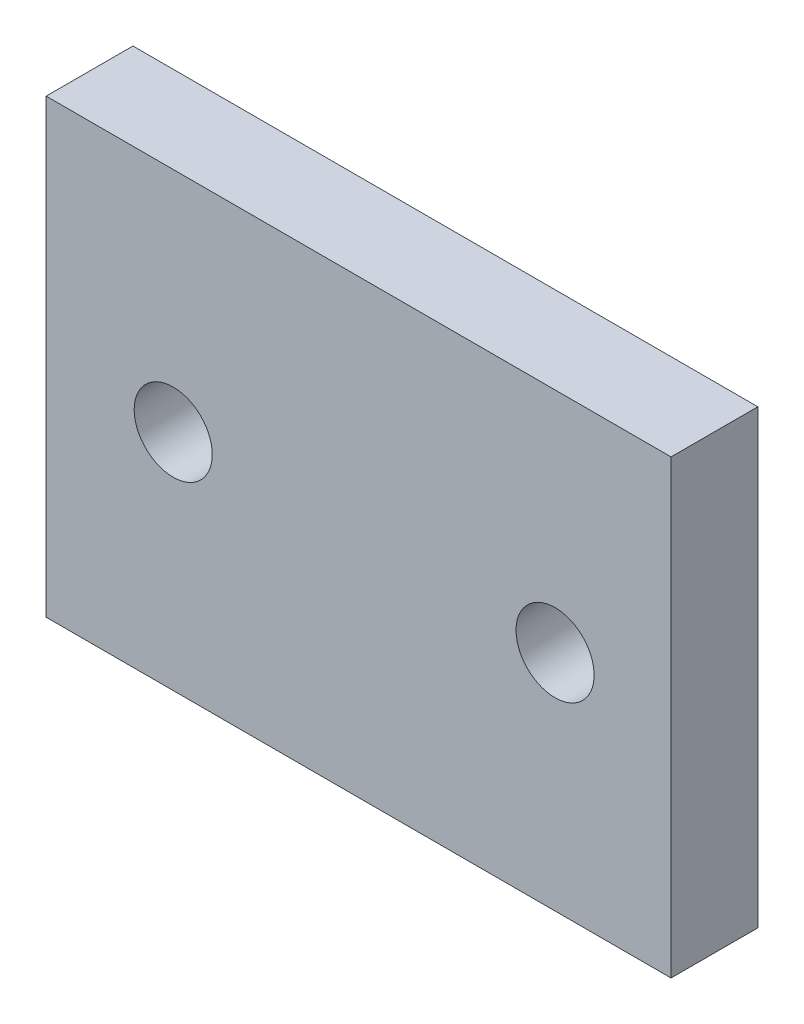
SolidWorks part; units mm, degrees
ref_plane "Plan de face" through (0, 0, 0) normal (0, 0, 1) x (1, 0, 0)
ref_plane "Plan de dessus" through (0, 0, 0) normal (0, 1, 0) x (1, 0, 0)
ref_plane "Plan de droite" through (0, 0, 0) normal (1, 0, 0) x (0, 0, -1)
sketch "Esquisse1" plane through (0, 0, 0) normal (0, 0, 1) x (1, 0, 0)
  line L1 (-18, -13) -> (18, -13)
  line L2 (-18, -13) -> (-18, 13)
  line L3 (-18, 13) -> (18, 13)
  line L4 (18, -13) -> (18, 13)
  line L5 (-18, -13) -> (18, 13) construction
  line L6 (-18, 13) -> (18, -13) construction
  point P0 (0, 0)
  dimension "D1" = 36
  dimension "D2" = 26
extrude "Boss.-Extru.1" add sketch "Esquisse1" along normal blind 5
hole_wizard "Dégagement M41" positions "Esquisse3" profile "Esquisse2" hole size "M4" standard "JIS" end condition through all
sketch "Esquisse3" plane through (0, 0, 0) normal (0, 0, -1) x (-1, 0, 0)
  point P0 (-11.3189, -0.1078)
  point P2 (10.6811, -0.105)
sketch "Esquisse2" plane through (11.3189, -0.1078, 0) normal (1, 0, 0) x (0, 1, 0)
  line L0 (0, 0) -> (0, 5)
  line L1 (0, 5) -> (2.25, 5)
  line L2 (2.25, 5) -> (2.25, 0)
  line L5 (2.25, 0) -> (0, 0)
  line L11 (0, -6.35) -> (0, 107.95) construction
  dimension "Diamètre du perçage jusqu'au prochain" = 4.5
  dimension "Profondeur du perçage jusqu'au prochain" = 5
